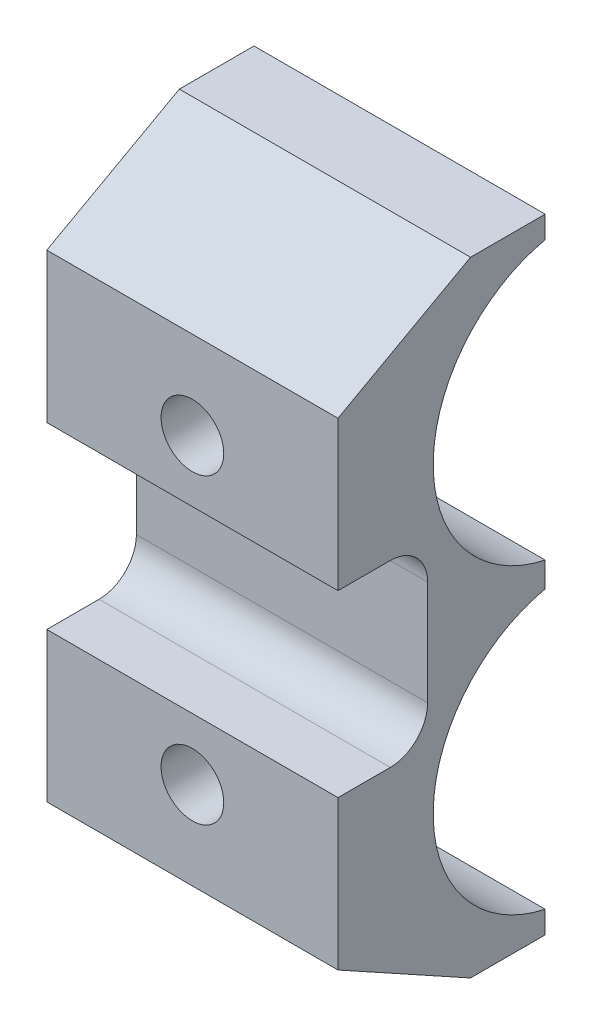
SolidWorks part; units mm, degrees
ref_plane "Top Plane" through (0, 0, 0) normal (0, 0, 1) x (1, 0, 0)
ref_plane "Right Plane" through (0, 0, 0) normal (0, 1, 0) x (1, 0, 0)
ref_plane "Front Plane" through (0, 0, 0) normal (1, 0, 0) x (0, 0, -1)
sketch "Sketch1" plane through (0, 0, 0) normal (1, 0, 0) x (0, 0, -1)
  line L0 (-15.875, 0) -> (17.9213, 0) construction
  line L1 (-15.875, -29.5905) -> (-15.875, 33.8515) construction
  line L2 (-15.875, -16) -> (0, -16) construction
  line L3 (-15.875, -16) -> (-15.875, 16)
  line L4 (-15.875, 16) -> (0, 16) construction
  line L5 (0, -16) -> (0, 16) construction
  line L6 (-15.875, -16) -> (-7, -20.9)
  line L7 (-7, -20.9) -> (-7, 20.9) construction
  line L8 (-15.875, 16) -> (-7, 20.9)
  line L9 (-7, -20.9) -> (-2, -20.9)
  line L10 (-2, -20.9) -> (-2, -19.4121)
  line L11 (-7, 20.9) -> (-2, 20.9)
  line L12 (-2, -0.8379) -> (-2, 0.8379)
  line L13 (-2, 19.4121) -> (-2, 20.9)
  circle A0 centre (0, -10.125) radius 9 construction
  circle A1 centre (0, 10.125) radius 9 construction
  arc A2 (-2, -0.8379) -> (-2, -19.4121) centre (0, -10.125) ccw
  arc A3 (-2, 19.4121) -> (-2, 0.8379) centre (0, 10.125) ccw
  circle A4 centre (0, -10.125) radius 9.5 construction
  point P20 (-7, 0)
  point P23 (-2, 0)
  dimension "D1" = 20.25
  dimension "D2" = 18
  dimension "D9" = 0.5
  dimension "D3" = 15.875
  dimension "D4" = 32
  dimension "D6" = 41.8
  dimension "D7" = 5
  dimension "D8" = 2
  dimension "D5" = 0.5
extrude "Boss-Extrude1" add sketch "Sketch1" along normal mid plane 19.5
sketch "Sketch2" plane through (0, 0, 15.875) normal (0, 0, 1) x (1, 0, 0)
  circle A0 centre (0, 10.125) radius 2.1
  circle A1 centre (0, -10.125) radius 2.1
  point P2 (0, 0)
  point P5 (0, 0)
  dimension "D1" = 4.2
extrude "Cut-Extrude1" cut sketch "Sketch2" against normal through all
sketch "Sketch3" plane through (-9.75, 0, 0) normal (-1, 0, 0) x (0, 0, 1)
  line L0 (-21.072, 0) -> (18.329, 0) construction
  line L1 (15.875, 6) -> (12.375, 6)
  line L2 (15.875, -16) -> (15.875, 16) construction
  line L3 (15.875, -6) -> (12.375, -6)
  line L4 (9.875, 3.5) -> (9.875, -3.5)
  line L5 (15.875, 6) -> (15.875, -6)
  arc A0 (12.375, 6) -> (9.875, 3.5) centre (12.375, 3.5) ccw
  arc A1 (12.375, -6) -> (9.875, -3.5) centre (12.375, -3.5) cw
  point P1 (0, 0)
  dimension "D1" = 5
  dimension "D3" = 2
  dimension "D2" = 1
  dimension "D4" = 12
extrude "Cut-Extrude2" cut sketch "Sketch3" against normal through all both and the other way through all
